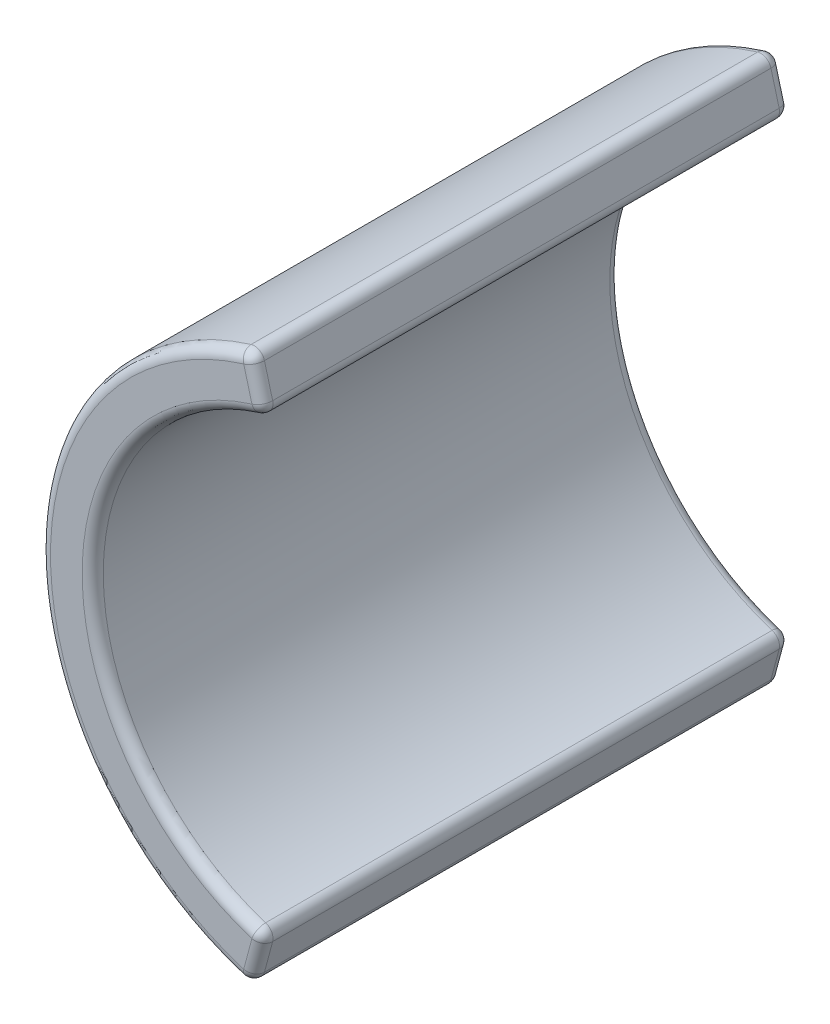
SolidWorks part; units mm, degrees
material "AISI 1020"
ref_plane "Frontal" through (0, 0, 0) normal (0, 0, 1) x (1, 0, 0)
ref_plane "Superior" through (0, 0, 0) normal (0, 1, 0) x (1, 0, 0)
ref_plane "Direito" through (0, 0, 0) normal (1, 0, 0) x (0, 0, -1)
sketch "Sketch1" plane through (0, 0, 0) normal (0, 1, 0) x (1, 0, 0)
  line L0 (-11, 0) -> (0, 0) construction
  line L1 (-13.5, 12.5) -> (-11, 12.5)
  line L2 (-13.5, 12.5) -> (-13.5, -12.5)
  line L3 (-13.5, -12.5) -> (-11, -12.5)
  line L4 (-11, 12.5) -> (-11, -12.5)
  line L5 (0, 0) -> (0, 13.21) construction
  dimension "D1" = 25
  dimension "D2" = 2.5
  dimension "D3" = 27
revolve "Revolve1" add sketch "Sketch1" angle 150 mid plane about L5
fillet "Fillet1" radius 0.5 12 edges at (-13.5, 0, -12.5) (-2.847, 10.6252, 0) (-3.4941, 13.04, 0) (-3.4941, -13.04, 0) (-11, 0, -12.5) (-13.5, 0, 12.5) (-2.847, -10.6252, 0) (-11, 0, 12.5) (-3.1705, -11.8326, -12.5) (-3.1705, -11.8326, 12.5) (-3.1705, 11.8326, -12.5) (-3.1705, 11.8326, 12.5)
